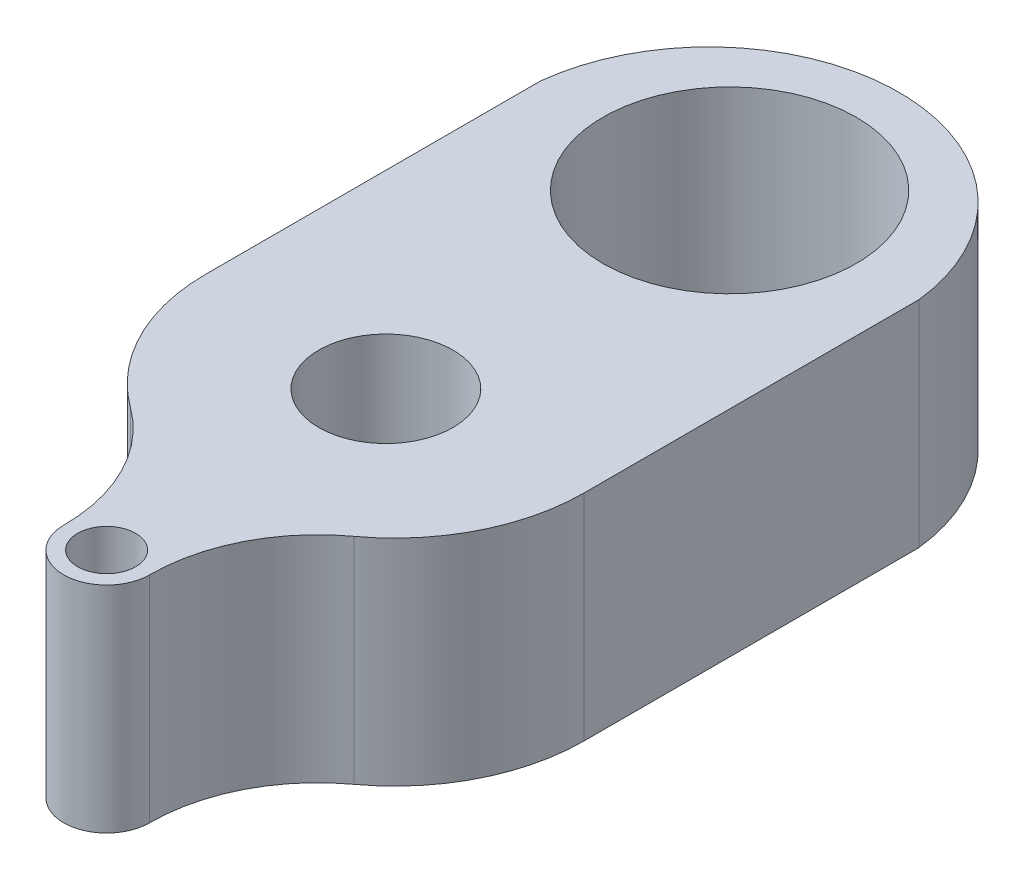
SolidWorks part; units mm, degrees
ref_plane "Front Plane" through (0, 0, 0) normal (0, 0, 1) x (1, 0, 0)
ref_plane "Top Plane" through (0, 0, 0) normal (0, 1, 0) x (1, 0, 0)
ref_plane "Right Plane" through (0, 0, 0) normal (1, 0, 0) x (0, 0, -1)
sketch "Sketch1" plane through (0, 0, 0) normal (0, 1, 0) x (1, 0, 0)
  line B0 (-1.1192, 3.683) -> (-1.1192, 1.7044)
  line B1 (0, 3.683) -> (0, -0.7855) construction
  line B2 (0, 0) -> (0.254, 0) construction
  line B3 (0, -0.254) -> (0, 3.683) construction
  line B4 (1.1192, 3.683) -> (1.1192, 1.7044)
  line B5 (0.254, 0) -> (-0.254, 0) construction
  arc B6 (1.1192, 1.7044) -> (0.6606, 0.8009) centre (0, 1.7044) cw
  arc B7 (0.6606, 0.8009) -> (0.254, 0) centre (1.2462, 0) ccw
  arc B8 (1.1192, 3.683) -> (-1.1192, 3.683) centre (0, 3.5604) ccw
  circle B9 centre (0, 0) radius 0.1714
  circle B10 centre (0, 0) radius 0.254
  arc B11 (-1.1192, 1.7044) -> (-0.6606, 0.8009) centre (0, 1.7044) ccw
  circle B12 centre (0, 3.683) radius 0.7493
  arc B13 (-0.6606, 0.8009) -> (-0.254, 0) centre (-1.2462, 0) cw
  circle B14 centre (0, 1.651) radius 0.3969
sketch_block_instance "BLACK drive shuttle block edit-1"
sketch_block "BLACK drive shuttle block edit" parameters "D3"=0.9922, "D4"=0.3429, "D5"=0.508, "D8"=1.4986, "D9"=1.7391, "D7"=1.4986, "D2"=0.254, "D6"=2.2384, "D10"=1.2966, "D11"=0.3699, "D1"=180
extrude "Boss-Extrude1" add sketch "Sketch1" along normal blind 1.27 contours B11 B13 B10 B7 B6 B4 B8 B0 B14 B12 | B10 B9
sketch "Sketch2" [suppressed] plane through (0, 1.27, 0) normal (0, 1, 0) x (1, 0, 0)
  line L0 (-1.1192, 3.683) -> (-1.1192, 1.7044) construction
  line L1 (0, 4.6863) -> (0, -0.254) construction
  arc A0 (-1.1192, 3.683) -> (-2.0358, 2.6937) centre (-2.1114, 3.683) cw
  arc A1 (-1.1192, 1.7044) -> (-2.0358, 2.6937) centre (-2.1114, 1.7044) ccw
  arc A2 (1.1192, 3.683) -> (-1.1192, 3.683) centre (0, 3.5604) ccw construction
  arc A3 (-0.254, 0) -> (0.254, 0) centre (0, 0) ccw construction
  arc A4 (1.1192, 1.7044) -> (2.0358, 2.6937) centre (2.1114, 1.7044) cw
  arc A5 (1.1192, 3.683) -> (2.0358, 2.6937) centre (2.1114, 3.683) ccw
  dimension "D1" = 0.9922
